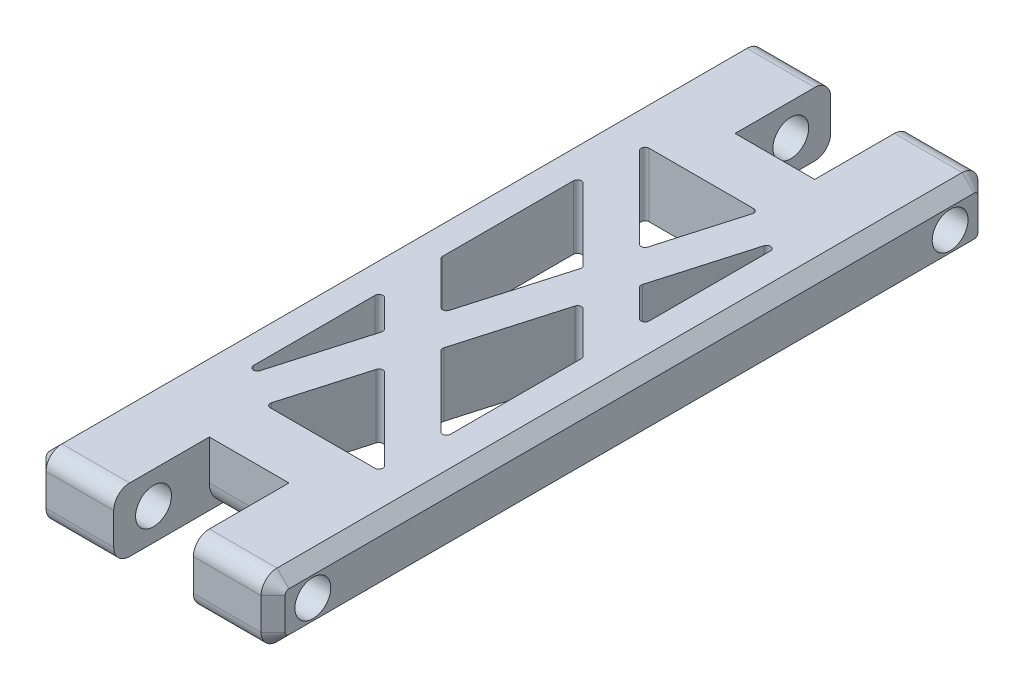
SolidWorks part; units mm, degrees
ref_plane "Front Plane" through (0, 0, 0) normal (0, 0, 1) x (1, 0, 0)
ref_plane "Top Plane" through (0, 0, 0) normal (0, 1, 0) x (1, 0, 0)
ref_plane "Right Plane" through (0, 0, 0) normal (1, 0, 0) x (0, 0, -1)
sketch "Sketch1" plane through (0, 0, 0) normal (0, 1, 0) x (1, 0, 0)
  line L1 (-15, 45) -> (15, 45)
  line L2 (-15, 45) -> (-15, -45)
  line L3 (-15, -45) -> (15, -45)
  line L4 (15, 45) -> (15, -45)
  line L5 (-15, 45) -> (15, -45) construction
  line L6 (-15, -45) -> (15, 45) construction
  point P0 (0, 0)
  dimension "D1" = 30
  dimension "D2" = 90
extrude "Boss-Extrude1" add sketch "Sketch1" along normal blind 8
sketch "Sketch2" plane through (0, 8, 0) normal (0, 1, 0) x (1, 0, 0)
  line L0 (15, 45) -> (-15, 45) construction
  line L1 (-5, 45) -> (5, 45)
  line L2 (-5, 45) -> (-5, 33)
  line L3 (-5, 33) -> (5, 33)
  line L4 (5, 45) -> (5, 33)
  line L5 (-15, -45) -> (15, -45) construction
  line L6 (5, -45) -> (-5, -45)
  line L7 (5, -45) -> (5, -33)
  line L8 (5, -33) -> (-5, -33)
  line L9 (-5, -45) -> (-5, -33)
  line L10 (15, -45) -> (15, 45) construction
  dimension "D1" = 10
  dimension "D2" = 10
  dimension "D3" = 10
  dimension "D4" = 12
  dimension "D5" = 12
  dimension "D6" = 10
extrude "Cut-Extrude1" cut sketch "Sketch2" against normal blind 8
sketch "Sketch3" plane through (15, 0, 0) normal (1, 0, 0) x (0, 0, -1)
  line L0 (-45, 8) -> (-45, 0) construction
  line L1 (-45, 8) -> (45, 8) construction
  circle A0 centre (-40, 4) radius 2.25
  dimension "D1" = 4.5
  dimension "D2" = 5
  dimension "D3" = 4
extrude "Cut-Extrude2" cut sketch "Sketch3" against normal through all
mirror "Mirror1" about plane through (0, 0, 0) normal (0, 0, 1) of "Cut-Extrude2"
fillet "Fillet1" radius 2 8 edges at (10, 0, -45) (10, 8, -45) (-10, 8, -45) (-10, 0, -45) (-10, 8, 45) (-10, 0, 45) (10, 0, 45) (10, 8, 45)
sketch "Sketch4" plane through (0, 8, 0) normal (0, 1, 0) x (1, 0, 0)
  line L0 (5, 26) -> (-10, 26)
  line L1 (-10, 26) -> (1.6418, 14.3582)
  line L2 (10, 6) -> (10, 26)
  line L3 (-10, -6) -> (-10, -26)
  line L4 (-5, -26) -> (10, -26)
  line L5 (10, -26) -> (-1.6418, -14.3582)
  line L6 (15, -43) -> (15, 43) construction
  line L7 (-15, 43) -> (-15, -43) construction
  line L8 (-10, 18.9289) -> (-10, 1.0711)
  line L9 (-10, 1.0711) -> (-3.9393, -4.9896)
  line L10 (9.8408, -18.7697) -> (9.8408, -0.9118)
  line L11 (9.8408, -0.9118) -> (3.9393, 4.9896)
  line L12 (-5, 33) -> (5, 33) construction
  line L13 (5, -33) -> (-5, -33) construction
  line L14 (5, 26) -> (1.6418, 14.3582)
  line L15 (-5, -26) -> (-1.6418, -14.3582)
  line L16 (-0.0587, -8.8702) -> (3.9393, 4.9896)
  line L18 (5.5224, 10.4776) -> (10, 6)
  line L19 (0.0587, 8.8702) -> (-10, 18.9289)
  line L20 (-0.0587, -8.8702) -> (9.8408, -18.7697)
  line L21 (-5.5224, -10.4776) -> (-10, -6)
  line L22 (-5.5224, -10.4776) -> (-10, -26)
  line L23 (0.0587, 8.8702) -> (-3.9393, -4.9896)
  line L24 (5.5224, 10.4776) -> (10, 26)
  dimension "D1" = 5
  dimension "D2" = 5
  dimension "D3" = 5
  dimension "D4" = 45
  dimension "D5" = 45
  dimension "D6" = 5
  dimension "D7" = 5
  dimension "D8" = 7
  dimension "D9" = 7
  dimension "D10" = 20
  dimension "D11" = 20
  dimension "D12" = 15
  dimension "D13" = 14
extrude "Cut-Extrude3" cut sketch "Sketch4" against normal through all
fillet "Fillet2" radius 3 2 edges at (0, 0, -33) (0, 0, 33)
chamfer "Chamfer1" distance 1.5 angle 45 16 edges at (15, 8, 0) (15, 7.4142, 44.4142) (15, 7.4142, -44.4142) (15, 4, 45) (15, 4, -45) (15, 0.5858, 44.4142) (15, 0.5858, -44.4142) (15, 0, 0) (-15, 0, 0) (-15, 0.5858, -44.4142) (-15, 0.5858, 44.4142) (-15, 4, -45) (-15, 4, 45) (-15, 7.4142, -44.4142) (-15, 7.4142, 44.4142) (-15, 8, 0)
fillet "Fillet3" radius 0.5 20 edges at (10, 4, -6) (10, 4, -26) (5.5224, 4, -10.4776) (3.9393, 4, -4.9896) (9.8408, 4, 0.9118) (9.8408, 4, 18.7697) (10, 4, 26) (-1.6418, 4, 14.3582) (-5, 4, 26) (-0.0587, 4, 8.8702) (5, 4, -26) (-10, 4, -26) (1.6418, 4, -14.3582) (0.0587, 4, -8.8702) (-3.9393, 4, 4.9896) (-10, 4, -18.9289) (-10, 4, -1.0711) (-5.5224, 4, 10.4776) (-10, 4, 26) (-10, 4, 6)
